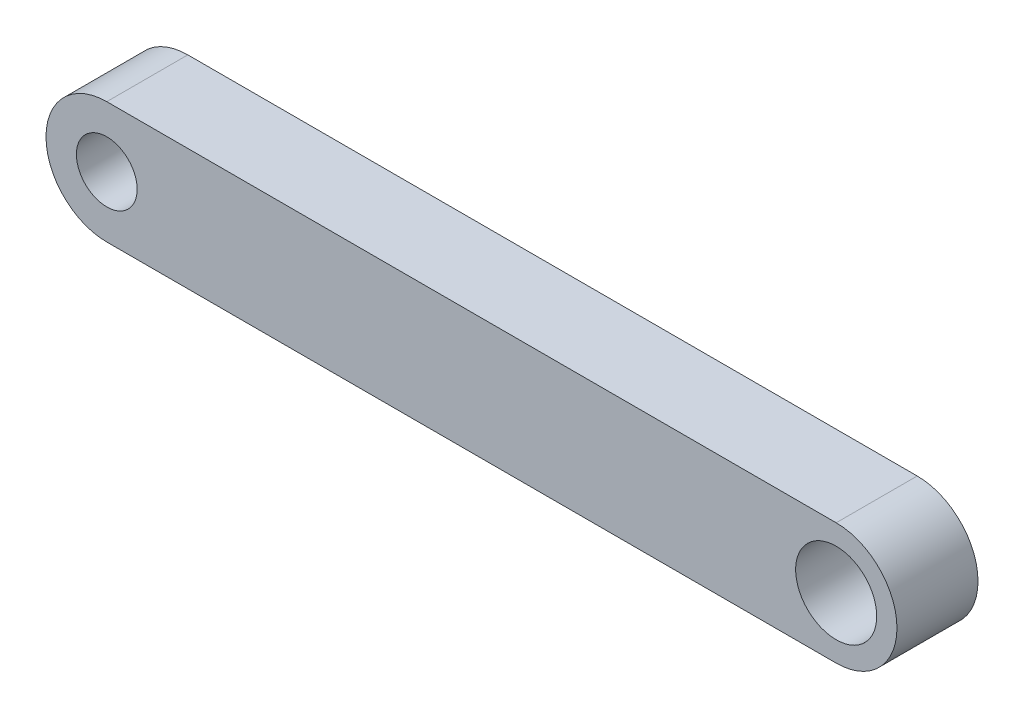
SolidWorks part; units mm, degrees
ref_plane "Front Plane" through (0, 0, 0) normal (0, 0, 1) x (1, 0, 0)
ref_plane "Top Plane" through (0, 0, 0) normal (0, 1, 0) x (1, 0, 0)
ref_plane "Right Plane" through (0, 0, 0) normal (1, 0, 0) x (0, 0, -1)
sketch "Sketch1" plane through (0, 0, 0) normal (0, 0, 1) x (1, 0, 0)
  line L0 (0, 3) -> (-36, 3)
  line L1 (0, -3) -> (-36, -3)
  line L2 (-18, 3) -> (-18, -3) construction
  line L3 (0, 3) -> (0, -3) construction
  circle A0 centre (0, 0) radius 2
  arc A1 (0, -3) -> (0, 3) centre (0, 0) ccw
  arc A2 (-36, -3) -> (-36, 3) centre (-36, 0) cw
  circle A3 centre (-36, 0) radius 1.5
  dimension "D1" = 4
  dimension "D2" = 6
  dimension "D4" = 3
  dimension "D3" = 36
extrude "Boss-Extrude1" add sketch "Sketch1" along normal blind 4
